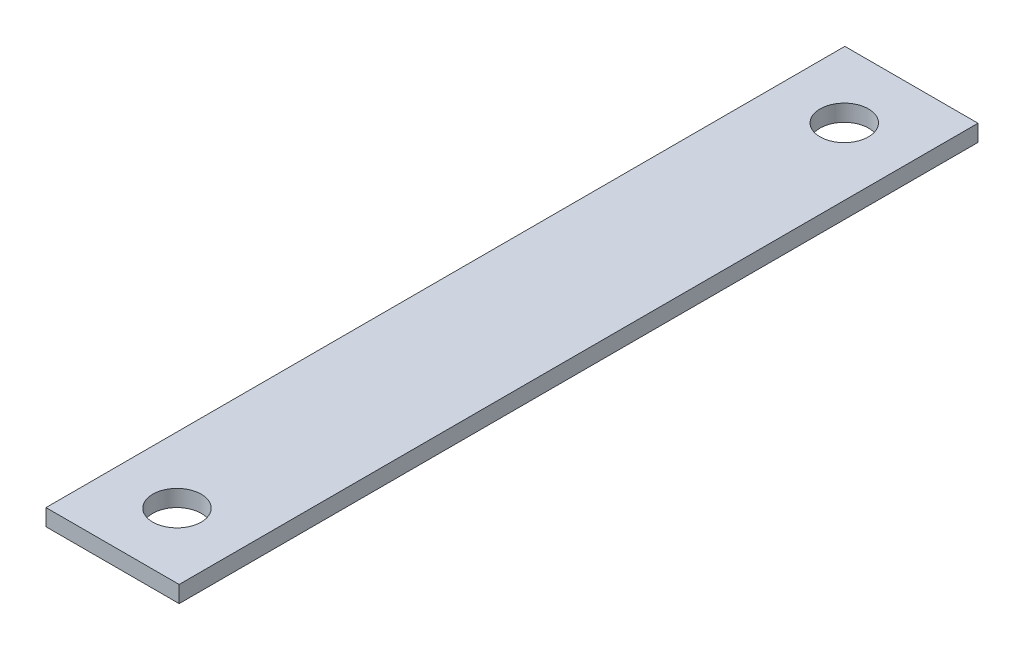
SolidWorks part; units mm, degrees
ref_plane "Front Plane" through (0, 0, 0) normal (0, 0, 1) x (1, 0, 0)
ref_plane "Top Plane" through (0, 0, 0) normal (0, 1, 0) x (1, 0, 0)
ref_plane "Right Plane" through (0, 0, 0) normal (1, 0, 0) x (0, 0, -1)
sketch "Sketch1" plane through (0, 0, 0) normal (0, 1, 0) x (1, 0, 0)
  line L1 (0, 101.5375) -> (12.7, 101.5375)
  line L2 (0, 101.5375) -> (0, 25.3375)
  line L3 (0, 25.3375) -> (12.7, 25.3375)
  line L4 (12.7, 101.5375) -> (12.7, 25.3375)
  circle A0 centre (6.2932, 95.1875) radius 2.31
  circle A5 centre (6.2932, 31.5375) radius 2.31
  point P4 (0, 0)
  dimension "D1" = 12.7
  dimension "D2" = 76.2
extrude "Boss-Extrude1" add sketch "Sketch1" along normal blind 1.5875
